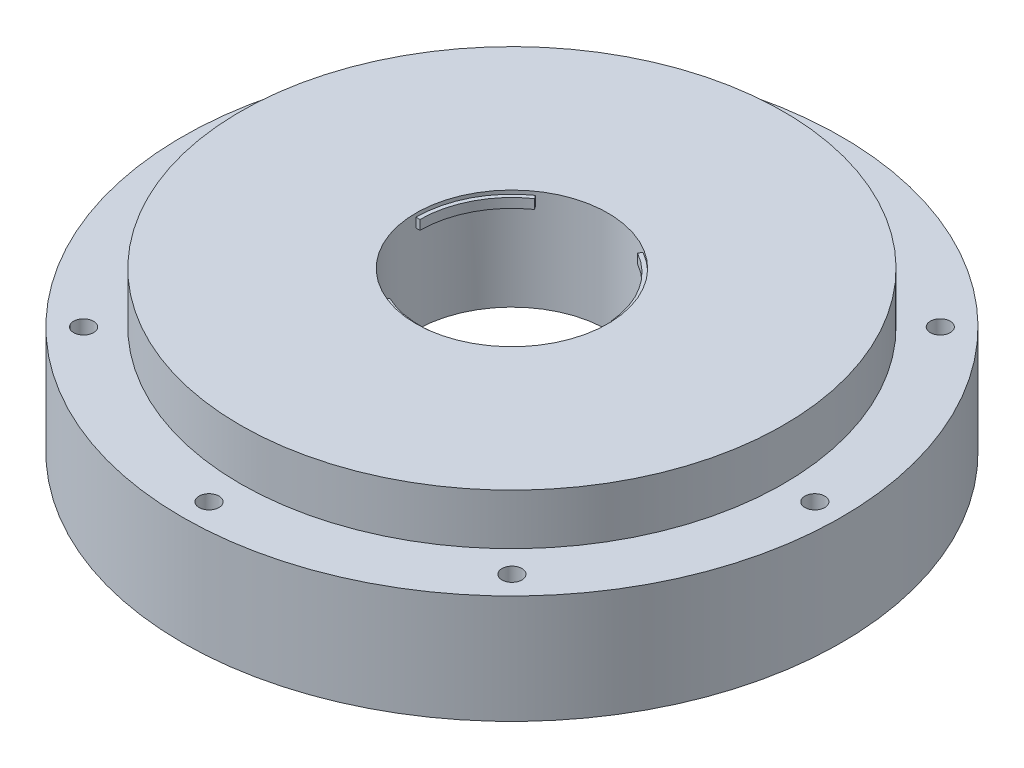
SolidWorks part; units mm, degrees
ref_plane "Front Plane" through (0, 0, 0) normal (0, 0, 1) x (1, 0, 0)
ref_plane "Top Plane" through (0, 0, 0) normal (0, 1, 0) x (1, 0, 0)
ref_plane "Right Plane" through (0, 0, 0) normal (1, 0, 0) x (0, 0, -1)
sketch "Sketch1" plane through (0, 0, 0) normal (0, 1, 0) x (1, 0, 0)
  line L0 (0, 83.635) -> (0, -83.635) construction
  circle A0 centre (0, 0) radius 65
  circle A1 centre (0, 0) radius 91
  circle A2 centre (0, 83.635) radius 2.75
  circle A3 centre (59.1389, 59.1389) radius 2.75
  circle A4 centre (83.635, 0) radius 2.75
  circle A5 centre (59.1389, -59.1389) radius 2.75
  circle A6 centre (0, -83.635) radius 2.75
  circle A7 centre (-59.1389, -59.1389) radius 2.75
  circle A8 centre (-83.635, 0) radius 2.75
  circle A9 centre (-59.1389, 59.1389) radius 2.75
  point P24 (0, 0)
  dimension "D1" = 130
  dimension "D2" = 26
  dimension "D3" = 167.27
  dimension "D4" = 5.5
  dimension "D5" = 8
extrude "Boss-Extrude1" add sketch "Sketch1" along normal blind 30
sketch "Sketch2" plane through (0, 30, 0) normal (0, 1, 0) x (1, 0, 0)
  circle A0 centre (0, 0) radius 75
  circle A1 centre (0, 0) radius 26.5
  dimension "D1" = 150
  dimension "D2" = 53
extrude "Boss-Extrude2" add sketch "Sketch2" along normal blind 14 and the other way blind 14
sketch "Sketch5" plane through (0, 0, 0) normal (0, 0, 1) x (1, 0, 0)
  line L0 (-26.5, 44) -> (-26.5, 43)
  line L1 (26.5, 44) -> (-26.5, 44) construction
  line L2 (75, 44) -> (-75, 44) construction
  line L3 (-26.5, 43) -> (-26.5, 40.4)
  line L4 (-26.5, 40.4) -> (-25.4, 40.4)
  line L5 (-25.4, 40.4) -> (-25.4, 43)
  line L6 (-25.4, 43) -> (-26.5, 43)
  line L7 (0, 48.2118) -> (0, 30.5841) construction
  point P6 (0, 48.2118)
  dimension "D1" = 1
  dimension "D2" = 2.6
  dimension "D3" = 1.1
revolve "Revolve1" add sketch "Sketch5" angle 55 about L7
pattern_circular "CirPattern1" count 3 over 360 about axis through (0, 0, 0) along (0, 1, 0) of "Revolve1"
